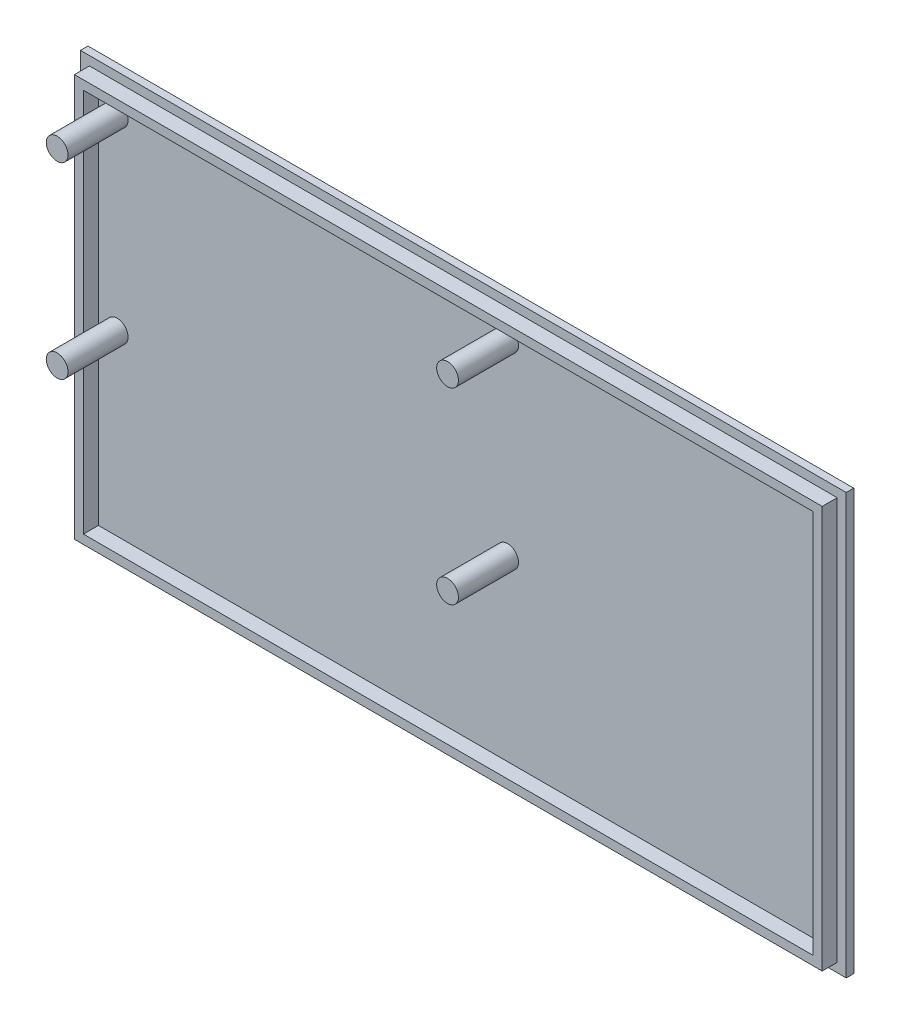
SolidWorks part; units mm, degrees
ref_plane "Front Plane" through (0, 0, 0) normal (0, 0, 1) x (1, 0, 0)
ref_plane "Top Plane" through (0, 0, 0) normal (0, 1, 0) x (1, 0, 0)
ref_plane "Right Plane" through (0, 0, 0) normal (1, 0, 0) x (0, 0, -1)
sketch "Sketch1" plane through (0, 0, 0) normal (0, 0, 1) x (1, 0, 0)
  line L1 (-51, -28) -> (51, -28)
  line L2 (-51, -28) -> (-51, 28)
  line L3 (-51, 28) -> (51, 28)
  line L4 (51, -28) -> (51, 28)
  line L5 (-51, -28) -> (51, 28) construction
  line L6 (-51, 28) -> (51, -28) construction
  point P0 (0, 0)
  dimension "D1" = 102
  dimension "D2" = 56
extrude "PANEL" add sketch "Sketch1" along normal blind 1
sketch "Sketch2" plane through (0, 0, 1) normal (0, 0, 1) x (1, 0, 0)
  line L0 (51, 28) -> (-51, 28) construction
  line L1 (-49.8, -26.8) -> (49.8, -26.8)
  line L2 (-49.8, -26.8) -> (-49.8, 26.8)
  line L3 (-49.8, 26.8) -> (49.8, 26.8)
  line L4 (49.8, -26.8) -> (49.8, 26.8)
  line L5 (-49.8, -26.8) -> (49.8, 26.8) construction
  line L6 (-49.8, 26.8) -> (49.8, -26.8) construction
  line L7 (51, -28) -> (51, 28) construction
  line L9 (-48.6, -25.6) -> (48.6, -25.6)
  line L10 (-48.6, -25.6) -> (-48.6, 25.6)
  line L11 (-48.6, 25.6) -> (48.6, 25.6)
  line L12 (48.6, -25.6) -> (48.6, 25.6)
  line L13 (-48.6, -25.6) -> (48.6, 25.6) construction
  line L14 (-48.6, 25.6) -> (48.6, -25.6) construction
  point P0 (0, 0)
  point P10 (0, 0)
  dimension "D1" = 1.2
  dimension "D2" = 1.2
  dimension "D3" = 1.2
  dimension "D4" = 1.2
extrude "MOUNTS" add sketch "Sketch2" along normal blind 2
sketch "Sketch3" plane through (0, 0, 1) normal (0, 0, 1) x (1, 0, 0)
  line L4 (-46.1, 23.1) -> (5.9, 23.1) construction
  line L5 (-46.1, 23.1) -> (-46.1, -1.9) construction
  line L6 (-46.1, -1.9) -> (5.9, -1.9) construction
  line L7 (5.9, 23.1) -> (5.9, -1.9) construction
  line L8 (48.6, 25.6) -> (-48.6, 25.6) construction
  line L9 (-48.6, 25.6) -> (-48.6, -25.6) construction
  circle A0 centre (-46.1, 23.1) radius 1.45
  circle A1 centre (-46.1, -1.9) radius 1.45
  circle A2 centre (5.9, 23.1) radius 1.45
  circle A3 centre (5.9, -1.9) radius 1.45
  dimension "D1" = 2.5
  dimension "D4" = 25
  dimension "D5" = 2.9
  dimension "D3" = 52
  dimension "D2" = 2.5
extrude "ESP_MOUNTS" add sketch "Sketch3" along normal blind 8
